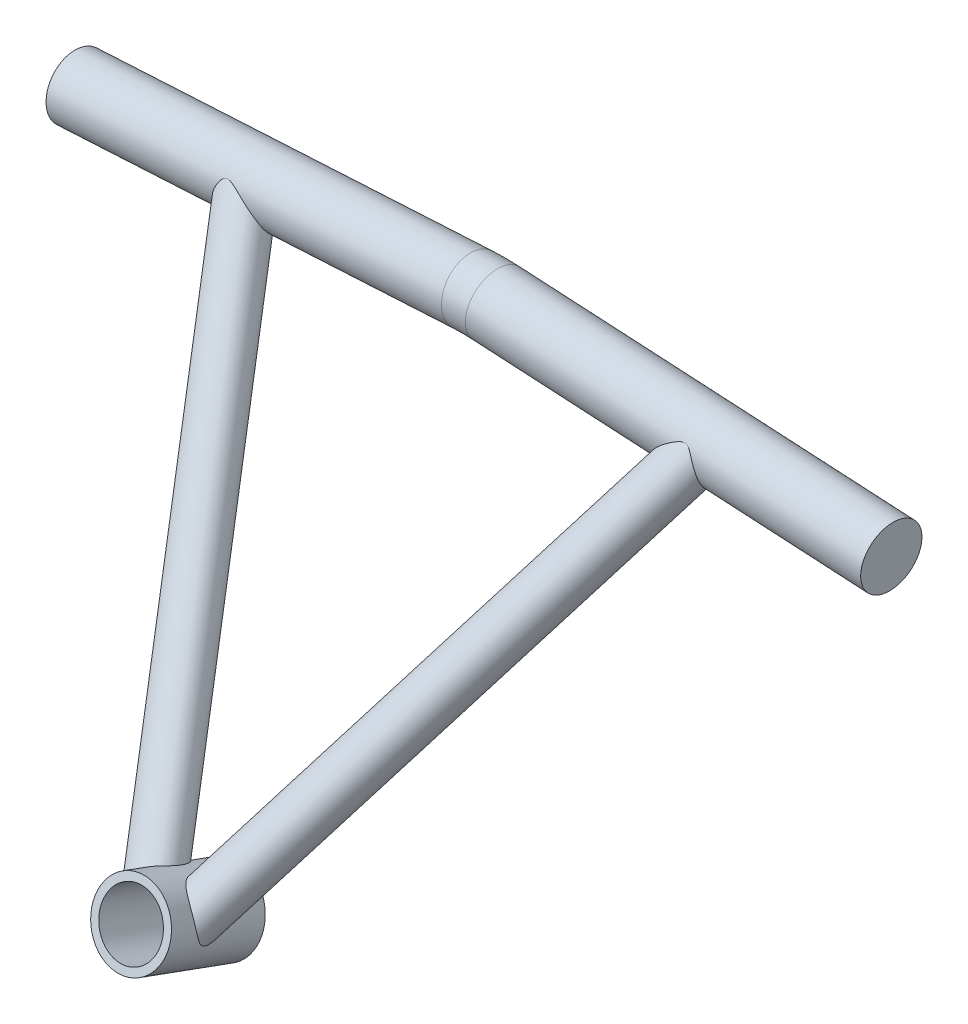
SolidWorks part; units mm, degrees
material "AISI 4130 Steel, normalized at 870C"
ref_plane "Front Plane" through (0, 0, 0) normal (0, 0, 1) x (1, 0, 0)
ref_plane "Top Plane" through (0, 0, 0) normal (0, 1, 0) x (1, 0, 0)
ref_plane "Right Plane" through (0, 0, 0) normal (1, 0, 0) x (0, 0, -1)
sketch "Sketch3" plane through (0, 0, 0) normal (0, 1, 0) x (1, 0, 0)
  line L0 (-5.08, -6.35) -> (5.08, -6.35) construction
  line L2 (0, -88.2205) -> (0, 88.2205) construction
  line L3 (5.08, 0) -> (-5.08, 0) construction
  dimension "D1" = 5.08
  dimension "D2" = 10.16
  dimension "D3" = 6.35
  dimension "D4" = 10.16
  dimension "D5" = 5.08
ref_plane "Plane1" through (0, 3.1268, 3.7263) normal (0, 0.6428, 0.766) x (1, 0, 0)
ref_plane "Plane3" through (0, 0, 0) normal (0, 0.342, 0.9397) x (-1, 0, 0)
sketch "Sketch1" plane through (0, 0, 0) normal (0, 0.342, 0.9397) x (1, 0, 0)
  circle A0 centre (0, 0) radius 15.875
  dimension "D1" = 31.75
extrude "Boss-Extrude1" add sketch "Sketch1" along normal mid plane 41.402 contours A0
sketch "Sketch4" plane through (0, 3.1268, 3.7263) normal (0, 0.6428, 0.766) x (1, 0, 0)
  line L0 (-5.08, -4.0817) -> (-96.7686, 201.8543)
  line L2 (0, -24.1976) -> (0, 24.1976) construction
  dimension "D2" = 24
  dimension "D3" = 225.425
sweep "Sweep1" add path "Sketch4" circular profile diameter 19.05 parameters "D3"=19.05
sketch "Sketch15" plane through (0, 3.1268, 3.7263) normal (0, 0.6428, 0.766) x (1, 0, 0)
  line L0 (5.08, -4.0817) -> (96.7686, 201.8543)
  line L1 (0, -87.2383) -> (0, 87.2383) construction
  dimension "D1" = 225.425
  dimension "D2" = 24
sweep "Sweep2" add path "Sketch15" circular profile diameter 19.05 parameters "D3"=19.05
sketch "Sketch2" plane through (0, -7.0802, -19.4526) normal (0, -0.342, -0.9397) x (-1, 0, 0)
  circle A0 centre (0, 0) radius 12.7
  dimension "D1" = 25.4
extrude "Cut-Extrude1" cut sketch "Sketch2" against normal up to next
sketch "Sketch36" plane through (-91.0124, 156.5926, -131.3968) normal (-0.4067, 0.6998, -0.5872) x (0.9135, 0.3116, -0.2614)
  circle A0 centre (-6.3009, -4.8645) radius 7.9375
  dimension "D1" = 15.875
extrude "Cut-Extrude2" cut sketch "Sketch36" against normal blind 127
sketch "Sketch37" plane through (91.0124, 156.5926, -131.3968) normal (0.4067, 0.6998, -0.5872) x (0.9135, -0.3116, 0.2614)
  circle A0 centre (6.3009, -4.8645) radius 7.9375
  dimension "D1" = 15.875
extrude "Cut-Extrude3" cut sketch "Sketch37" against normal blind 127
ref_plane "Plane2" through (0, 0, -127) normal (0, 0, 1) x (1, 0, 0)
sketch "Sketch40" plane through (-106.934, 0, -127) normal (0, 0, 1) x (1, 0, 0)
  line L2 (106.934, -101.5068) -> (106.934, 101.5068) construction
  line L3 (101.9947, 159.6287) -> (-62.0894, 150.498)
  line L4 (111.8733, 159.6287) -> (275.9574, 150.498)
  arc A0 (101.9947, 159.6287) -> (111.8733, 159.6287) centre (106.934, 70.866) cw
  point P0 (106.934, 159.766)
  point P4 (0, 0)
  point P7 (106.934, 159.766)
  dimension "D1" = 164.338
  dimension "D3" = 88.9
  dimension "D2" = 164.338
  dimension "D4" = 9.8786
sweep "Sweep3" add path "Sketch40" circular profile diameter 25.4 parameters "D3"=25.4
